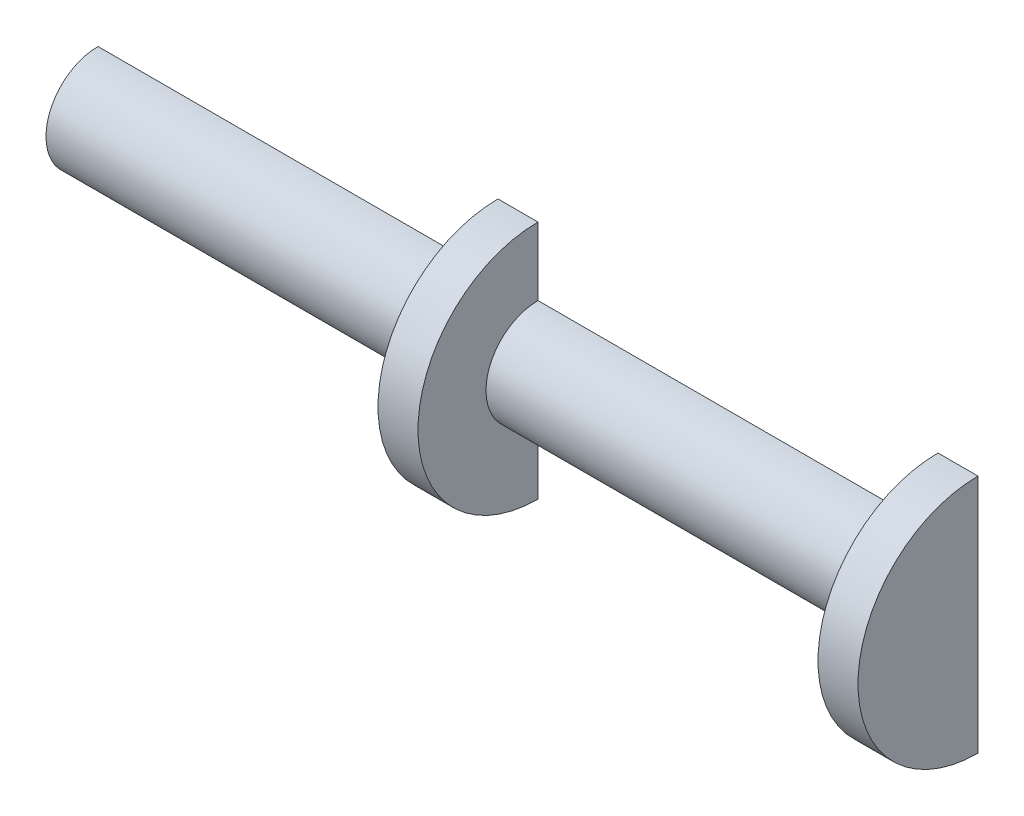
SolidWorks part; units mm, degrees
ref_plane "Front Plane" through (0, 0, 0) normal (0, 0, 1) x (1, 0, 0)
ref_plane "Top Plane" through (0, 0, 0) normal (0, 1, 0) x (1, 0, 0)
ref_plane "Right Plane" through (0, 0, 0) normal (1, 0, 0) x (0, 0, -1)
sketch "Sketch1" plane through (0, 0, 0) normal (0, 0, 1) x (1, 0, 0)
  line L1 (-55.88, 3.302) -> (55.88, 3.302)
  line L2 (-55.88, 3.302) -> (-55.88, 0)
  line L3 (-55.88, 0) -> (55.88, 0)
  line L4 (55.88, 3.302) -> (55.88, 0)
  line L5 (55, 0) -> (-55, 0) construction
  line L6 (0, -55) -> (0, 55) construction
  line L7 (-55.88, 0) -> (55.88, 0) construction
  point P4 (0, 3.302)
  dimension "D1" = 3.302
  dimension "D2" = 111.76
revolve "Revolve1" add sketch "Sketch1" angle 360 about L7
sketch "Sketch6" plane through (0, 0, 0) normal (0, 0, 1) x (1, 0, 0)
  line L0 (-27.94, 3.302) -> (-27.94, 7.62)
  line L1 (55.88, 3.302) -> (-55.88, 3.302) construction
  line L2 (-27.94, 7.62) -> (-25.4, 7.62)
  line L3 (-25.4, 7.62) -> (-25.4, 3.302)
  line L4 (-25.4, 3.302) -> (-27.94, 3.302)
  line L5 (0, -55) -> (0, 55) construction
  line L6 (-31.8784, 0) -> (55.88, 0) construction
  line L7 (27.94, 3.302) -> (25.4, 3.302)
  line L8 (27.94, 3.302) -> (27.94, 7.62)
  line L9 (27.94, 7.62) -> (25.4, 7.62)
  line L10 (25.4, 3.302) -> (25.4, 7.62)
  line L11 (55, 0) -> (-55, 0) construction
  line L12 (55.88, -3.302) -> (55.88, 3.302) construction
  line L13 (55.88, 3.302) -> (-55.88, 3.302) construction
  line L14 (-53.34, 3.302) -> (-55.88, 3.302)
  line L15 (-53.34, 3.302) -> (-53.34, 7.62)
  line L16 (-53.34, 7.62) -> (-55.88, 7.62)
  line L17 (-55.88, 3.302) -> (-55.88, 7.62)
  line L19 (53.34, 3.302) -> (55.88, 3.302)
  line L20 (53.34, 3.302) -> (53.34, 7.62)
  line L21 (53.34, 7.62) -> (55.88, 7.62)
  line L22 (55.88, 3.302) -> (55.88, 7.62)
  dimension "D1" = 25.4
  dimension "D2" = 2.54
  dimension "D3" = 4.318
  dimension "D4" = 25.4
  dimension "D5" = 2.54
  dimension "D6" = 4.318
  dimension "D7" = 4.318
  dimension "D8" = 2.54
  dimension "D9" = 25.4
  dimension "D10" = 4.318
  dimension "D11" = 2.54
  dimension "D12" = 25.4
revolve "Revolve2" add sketch "Sketch6" angle 360 about L6
sketch "Sketch7" plane through (0, 0, 0) normal (1, 0, 0) x (0, 0, -1)
  line L0 (0, 8.382) -> (0, -8.382) construction
  line L1 (0, 7.62) -> (7.62, 7.62)
  line L2 (0, 7.62) -> (0, -7.62)
  line L3 (0, -7.62) -> (7.62, -7.62)
  line L4 (7.62, 7.62) -> (7.62, -7.62)
  circle A0 centre (0, 0) radius 7.62 construction
extrude "Cut-Extrude1" cut sketch "Sketch7" against normal through all and the other way through all
sketch "Sketch8" plane through (0, 0, 0) normal (0, 0, 1) x (1, 0, 0)
  line L0 (0, -8.382) -> (0, 8.382) construction
  line L1 (-55.88, -7.62) -> (0, -7.62)
  line L2 (-55.88, -7.62) -> (-55.88, 7.62)
  line L3 (-55.88, 7.62) -> (0, 7.62)
  line L4 (0, -7.62) -> (0, 7.62)
extrude "Cut-Extrude2" cut sketch "Sketch8" along normal through all
